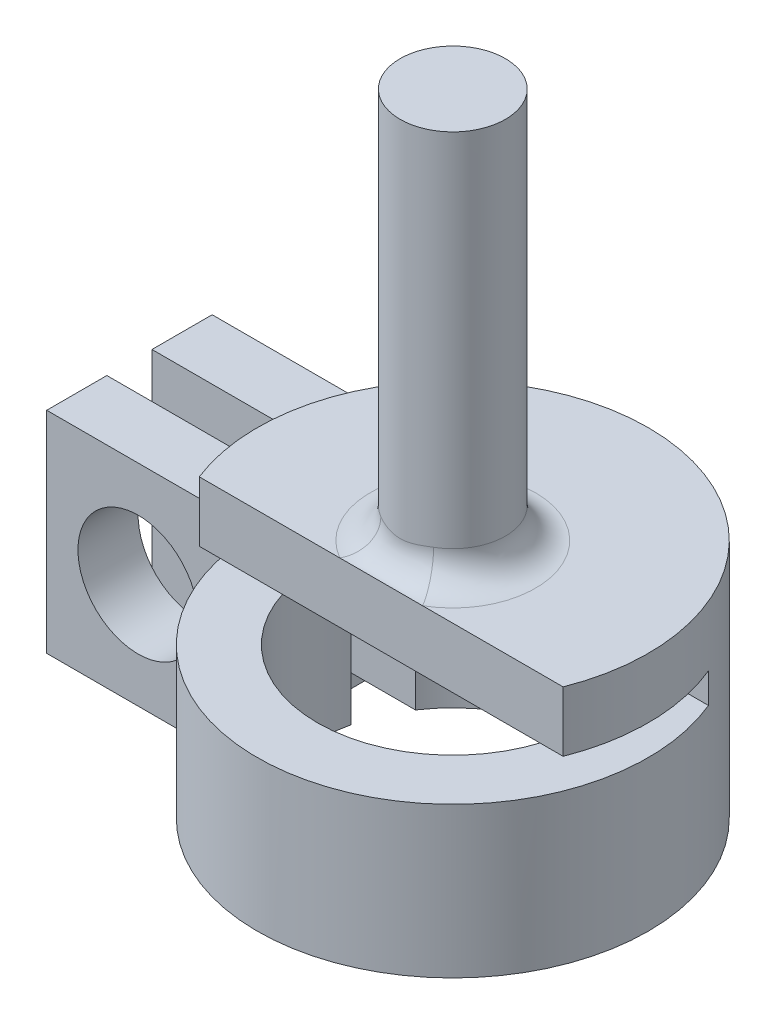
SolidWorks part; units mm, degrees
ref_plane "Front Plane" through (0, 0, 0) normal (0, 0, 1) x (1, 0, 0)
ref_plane "Top Plane" through (0, 0, 0) normal (0, 1, 0) x (1, 0, 0)
ref_plane "Right Plane" through (0, 0, 0) normal (1, 0, 0) x (0, 0, -1)
sketch "Sketch1" plane through (0, 0, 0) normal (0, 1, 0) x (1, 0, 0)
  line L0 (-4.6904, 4.5) -> (-12.5, 4.5)
  line L1 (-12.5, 4.5) -> (-12.5, 2.5)
  line L2 (-12.5, 2.5) -> (-3.7417, 2.5)
  line L3 (-4.3875, 1) -> (-12.5, 1)
  line L4 (-12.5, 1) -> (-12.5, -1)
  line L5 (-12.5, -1) -> (-6.4226, -1)
  line L6 (-4.5, 0) -> (0, 0) construction
  arc A0 (-4.3875, 1) -> (-3.7417, 2.5) centre (0, 0) ccw
  arc A1 (-6.4226, -1) -> (-4.6904, 4.5) centre (0, 0) ccw
  circle A2 centre (0, 0) radius 6.5 construction
  circle A3 centre (0, 0) radius 4.5 construction
  dimension "D1" = 9
  dimension "D2" = 2
  dimension "D3" = 2
  dimension "D4" = 1.5
  dimension "D5" = 2
  dimension "D6" = 8
extrude "Boss-Extrude1" add sketch "Sketch1" along normal blind 5
sketch "Sketch2" plane through (0, 0, 1) normal (0, 0, 1) x (1, 0, 0)
  line L0 (-9.4613, 5) -> (-9.4613, 0) construction
  line L1 (-12.5, 5) -> (-6.4226, 5) construction
  line L2 (-12.5, 0) -> (-6.4226, 0) construction
  circle A0 centre (-9.4613, 2.5) radius 2
  dimension "D1" = 4
sketch "Sketch3" plane through (0, 0, 1) normal (0, 0, 1) x (1, 0, 0)
  line L0 (-6.4226, 5) -> (-6.4226, 0) construction
  line L1 (-12.5, 5) -> (-6.4226, 5)
  line L2 (-12.5, 5) -> (-12.5, 6)
  line L3 (-12.5, 6) -> (-6.4226, 6)
  line L4 (-6.4226, 5) -> (-6.4226, 6)
  line L5 (-12.5, 0) -> (-6.4226, 0)
  line L6 (-12.5, 0) -> (-12.5, -1)
  line L7 (-12.5, -1) -> (-6.4226, -1)
  line L8 (-6.4226, 0) -> (-6.4226, -1)
  dimension "D1" = 1
  dimension "D2" = 1
extrude "Boss-Extrude2" add sketch "Sketch3" against normal up to surface (5.5 mm away) up to face at (-8.5952, 2.5, -4.5)
sketch "Sketch4" plane through (-12.5, 0, 0) normal (-1, 0, 0) x (0, 0, 1)
  line L0 (-4.5, 6) -> (1, 6) construction
  line L1 (-2.5, 6) -> (-1, 6)
  line L2 (-2.5, 6) -> (-2.5, -1)
  line L3 (-2.5, -1) -> (-1, -1)
  line L4 (-1, 6) -> (-1, -1)
  line L5 (-4.5, -1) -> (1, -1) construction
  line L6 (-2.5, 5) -> (-2.5, 0) construction
  line L7 (-1, 5) -> (-1, 0) construction
extrude "Cut-Extrude1" cut sketch "Sketch4" against normal blind 10
extrude "Cut-Extrude2" cut sketch "Sketch2" against normal blind 10
sketch "Sketch5" plane through (0, 5, 0) normal (0, 1, 0) x (1, 0, 0)
  line L0 (4.899, 2.5) -> (6, 2.5)
  line L1 (-6.4226, 2.5) -> (-3.7417, 2.5) construction
  line L2 (-6, 2.5) -> (-4.899, 2.5)
  arc A1 (-6.4226, -1) -> (-4.6904, 4.5) centre (0, 0) ccw construction
  arc A3 (6, 2.5) -> (-6, 2.5) centre (0, 0) ccw
  arc A4 (4.899, 2.5) -> (-4.899, 2.5) centre (0, 0) ccw
extrude "Boss-Extrude3" add sketch "Sketch5" along normal blind 1
sketch "Sketch6" plane through (0, 6, 0) normal (0, 1, 0) x (1, 0, 0)
  line L0 (-6.0484, -2.3804) -> (6.0484, -2.3804)
  arc A0 (6, 2.5) -> (-6, 2.5) centre (0, 0) ccw construction
  arc A1 (6.0484, -2.3804) -> (-6.0484, -2.3804) centre (0, 0) ccw
  point P5 (0, 0)
extrude "Boss-Extrude4" add sketch "Sketch6" along normal blind 2
sketch "Sketch7" plane through (0, 8, 0) normal (0, 1, 0) x (1, 0, 0)
  line L2 (-6.0484, -2.3804) -> (6.0484, -2.3804)
  line L3 (-6.0484, -2.3804) -> (6.0484, -2.3804) construction
  circle A0 centre (0, 0) radius 1.75
  arc A2 (6.0484, -2.3804) -> (-6.0484, -2.3804) centre (0, 0) ccw
  arc A3 (6.0484, -2.3804) -> (-6.0484, -2.3804) centre (0, 0) ccw construction
  point P2 (0, 0)
  point P3 (0, 0)
  point P4 (0, 0)
  point P5 (0, 0)
  point P6 (0, 0)
  point P7 (0, 0)
  point P8 (0, 0)
  point P12 (0, 0)
  point P13 (0, 0)
  point P14 (0, 0)
  dimension "D1" = 3.5
  dimension "D2" = 0
extrude "Boss-Extrude5" add sketch "Sketch7" along normal blind 13
fillet "Fillet1" radius 1 1 edges at (0, 8, 1.75)
